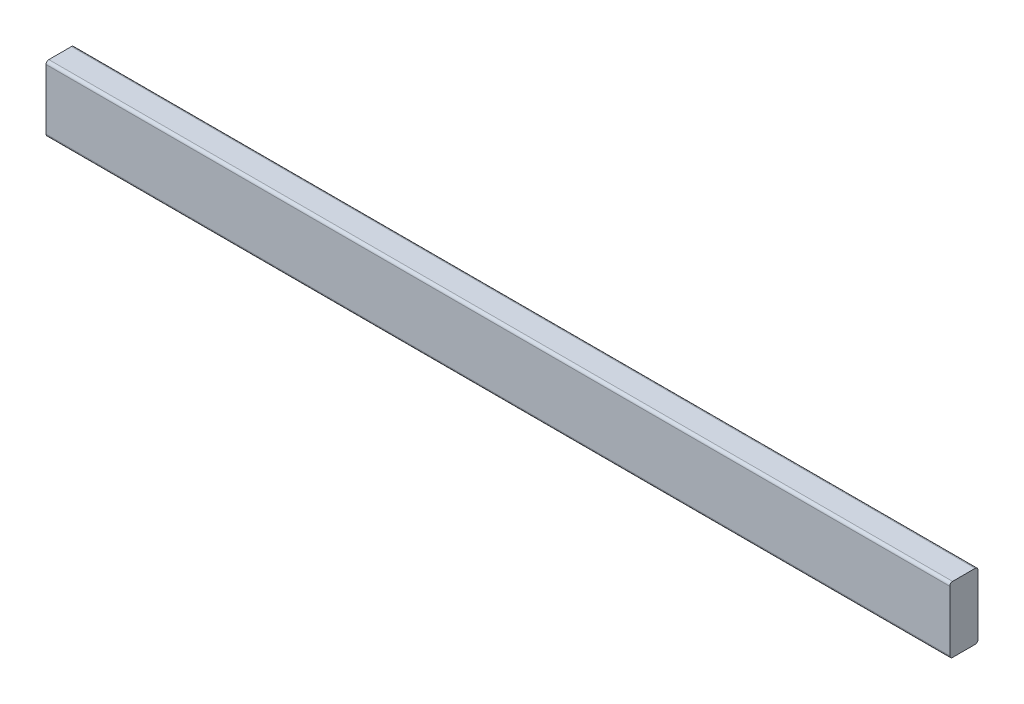
SolidWorks part; units mm, degrees
material "Maple"
ref_plane "Front Plane" through (0, 0, 0) normal (0, 0, 1) x (1, 0, 0)
ref_plane "Top Plane" through (0, 0, 0) normal (0, 1, 0) x (1, 0, 0)
ref_plane "Right Plane" through (0, 0, 0) normal (1, 0, 0) x (0, 0, -1)
sketch "Sketch1" plane through (0, 0, 0) normal (1, 0, 0) x (0, 0, -1)
  line L1 (-15.24, 44.45) -> (15.24, 44.45)
  line L2 (-19.05, 40.64) -> (-19.05, -40.64)
  line L3 (-15.24, -44.45) -> (15.24, -44.45)
  line L4 (19.05, 40.64) -> (19.05, -40.64)
  line L5 (-19.05, 44.45) -> (19.05, -44.45) construction
  line L6 (-19.05, -44.45) -> (19.05, 44.45) construction
  arc A0 (15.24, 44.45) -> (19.05, 40.64) centre (15.24, 40.64) cw
  arc A1 (15.24, -44.45) -> (19.05, -40.64) centre (15.24, -40.64) ccw
  arc A2 (-19.05, -40.64) -> (-15.24, -44.45) centre (-15.24, -40.64) ccw
  arc A3 (-15.24, 44.45) -> (-19.05, 40.64) centre (-15.24, 40.64) ccw
  point P0 (0, 0)
  dimension "D3" = 3.81
  dimension "D1" = 38.1
  dimension "D2" = 88.9
extrude "Boss-Extrude1" add sketch "Sketch1" along normal mid plane 1219.2
